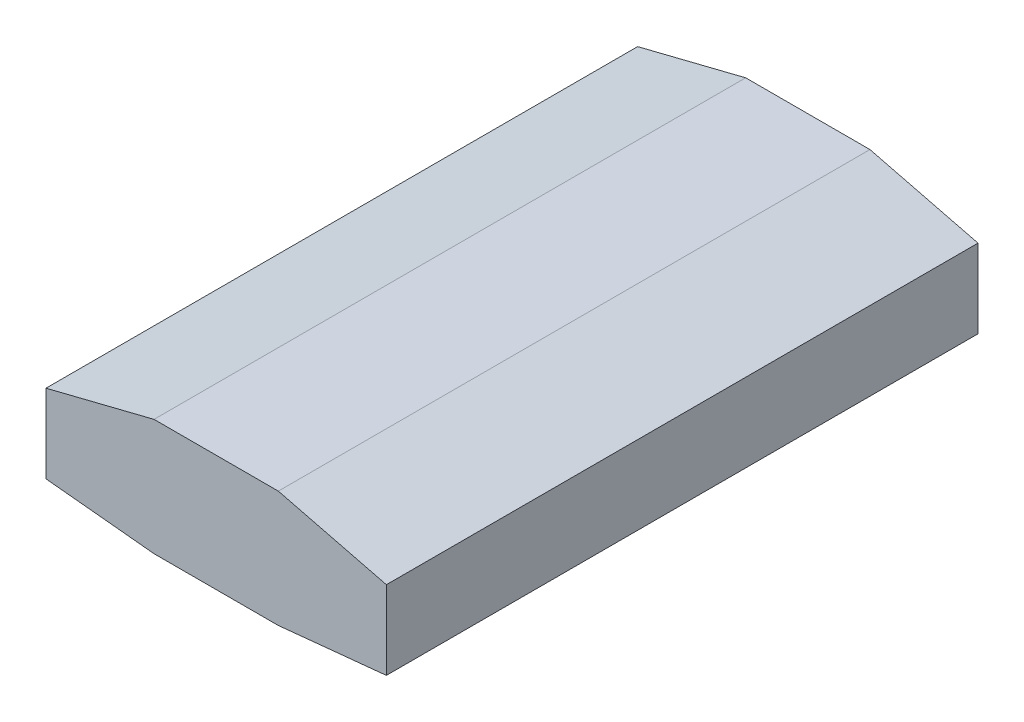
SolidWorks part; units mm, degrees
ref_plane "前视基准面" through (0, 0, 0) normal (0, 0, 1) x (1, 0, 0)
ref_plane "上视基准面" through (0, 0, 0) normal (0, 1, 0) x (1, 0, 0)
ref_plane "右视基准面" through (0, 0, 0) normal (1, 0, 0) x (0, 0, -1)
sketch "草图1" plane through (0, 0, 0) normal (0, 0, 1) x (1, 0, 0)
  line L1 (-31.5, 10.77) -> (31.5, 10.77)
  line L2 (-31.5, 10.77) -> (-31.5, -10.77)
  line L3 (-31.5, -10.77) -> (31.5, -10.77)
  line L4 (31.5, 10.77) -> (31.5, -10.77)
  line L5 (-31.5, 10.77) -> (31.5, -10.77) construction
  line L6 (-31.5, -10.77) -> (31.5, 10.77) construction
  point P0 (0, 0)
  dimension "D1" = 21.54
  dimension "D2" = 63
extrude "凸台-拉伸1" add sketch "草图1" along normal blind 109.5
sketch "草图2" plane through (0, 0, 109.5) normal (0, 0, 1) x (1, 0, 0)
  line L0 (11.5, 10.77) -> (31.5, 5.77)
  line L1 (31.5, 10.77) -> (-31.5, 10.77) construction
  line L2 (31.5, -10.77) -> (31.5, 10.77) construction
  line L3 (31.5, 5.77) -> (31.5, 10.77)
  line L4 (31.5, 10.77) -> (11.5, 10.77)
  line L5 (-31.5, 10.77) -> (-11.5, 10.77)
  line L6 (-11.5, 10.77) -> (-31.5, 5.77)
  line L7 (-31.5, 10.77) -> (-31.5, -10.77) construction
  line L8 (-31.5, 5.77) -> (-31.5, 10.77)
  line L9 (-31.5, -8.77) -> (-11.5, -10.77)
  line L10 (-31.5, -10.77) -> (31.5, -10.77) construction
  line L11 (-11.5, -10.77) -> (-31.5, -10.77)
  line L12 (-31.5, -10.77) -> (-31.5, -8.77)
  line L13 (31.5, -8.77) -> (11.5, -10.77)
  line L14 (11.5, -10.77) -> (31.5, -10.77)
  line L15 (31.5, -10.77) -> (31.5, -8.77)
  dimension "D1" = 20
  dimension "D2" = 20
  dimension "D3" = 5
  dimension "D4" = 5
  dimension "D5" = 20
  dimension "D6" = 2
  dimension "D7" = 20
  dimension "D8" = 2
extrude "切除-拉伸1" cut sketch "草图2" against normal through all
sketch "草图3" plane through (0, -10.77, 0) normal (0, -1, 0) x (1, 0, 0)
  line L0 (-7, 5) -> (7, 5) construction
  line L1 (-11.5, 0) -> (11.5, 0) construction
  circle A0 centre (-7, 5) radius 1
  circle A1 centre (7, 5) radius 1
  circle A2 centre (-7, 85) radius 1
  circle A3 centre (7, 85) radius 1
  point P4 (0, 5)
  dimension "D1" = 2
  dimension "D2" = 2
  dimension "D3" = 14
  dimension "D4" = 5
  dimension "D5" = 2
extrude "切除-拉伸2" cut sketch "草图3" against normal blind 5
